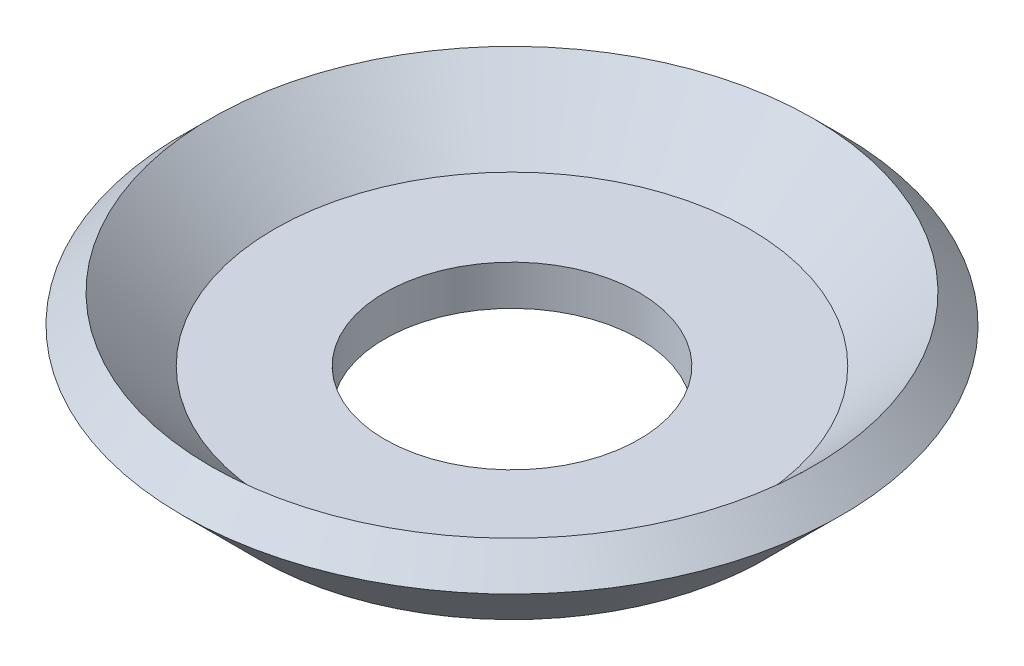
SolidWorks part; units mm, degrees
ref_plane "Front Plane" through (0, 0, 0) normal (0, 0, 1) x (1, 0, 0)
ref_plane "Top Plane" through (0, 0, 0) normal (0, 1, 0) x (1, 0, 0)
ref_plane "Right Plane" through (0, 0, 0) normal (1, 0, 0) x (0, 0, -1)
sketch "Sketch1" plane through (0, 0, 0) normal (1, 0, 0) x (0, 0, -1)
  line L0 (0, 0) -> (0, 15.7358) construction
  line L1 (-4.7625, 0) -> (-9.5113, 0)
  line L2 (-9.5113, 0) -> (-12.3397, 2.8284)
  line L3 (-12.3397, 2.8284) -> (-11.2791, 3.8891)
  line L4 (-11.2791, 3.8891) -> (-8.89, 1.5)
  line L5 (-8.89, 1.5) -> (-4.7625, 1.5)
  line L7 (-4.7625, 0) -> (-4.7625, 1.5)
  dimension "D1" = 1.5
  dimension "D2" = 1.5
  dimension "D3" = 135
  dimension "D4" = 4
  dimension "D5" = 17.78
  dimension "D6" = 9.525
revolve "Revolve1" add sketch "Sketch1" angle 360 about L0
